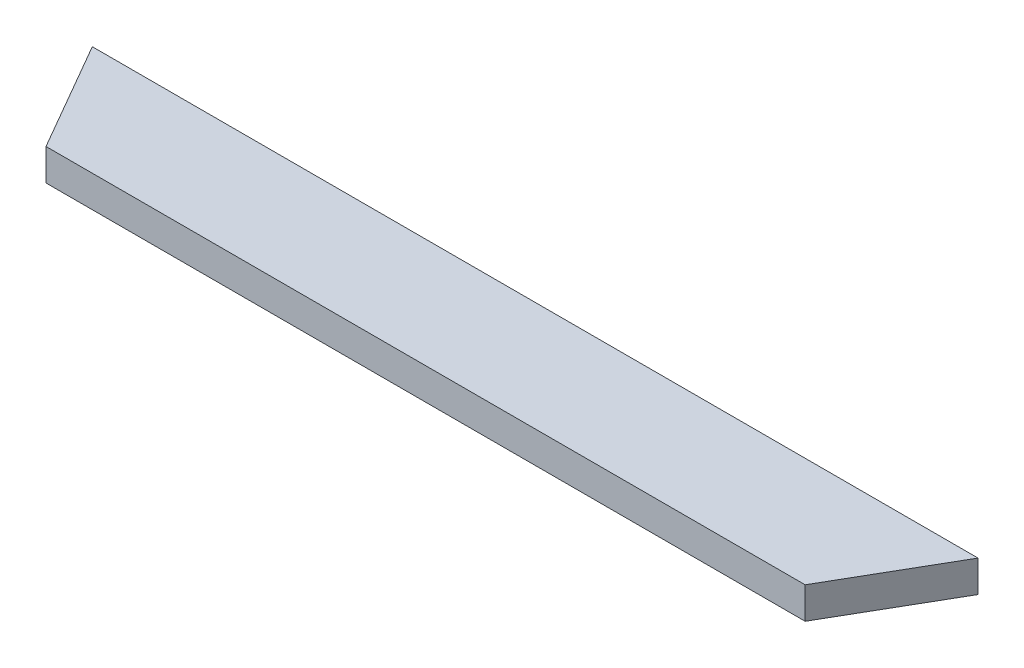
SolidWorks part; units mm, degrees
ref_plane "Front Plane" through (0, 0, 0) normal (0, 0, 1) x (1, 0, 0)
ref_plane "Top Plane" through (0, 0, 0) normal (0, 1, 0) x (1, 0, 0)
ref_plane "Right Plane" through (0, 0, 0) normal (1, 0, 0) x (0, 0, -1)
sketch "Sketch1" plane through (0, 0, 0) normal (0, 1, 0) x (1, 0, 0)
  line L0 (-600, 0) -> (600, 0)
  line L1 (600, 0) -> (700, 173.2051)
  line L2 (700, 173.2051) -> (-700, 173.2051)
  line L3 (-700, 173.2051) -> (-600, 0)
  point P3 (0, 0)
  dimension "D1" = 60
  dimension "D2" = 60
  dimension "D3" = 200
  dimension "D4" = 1200
extrude "Boss-Extrude1" add sketch "Sketch1" along normal blind 50
